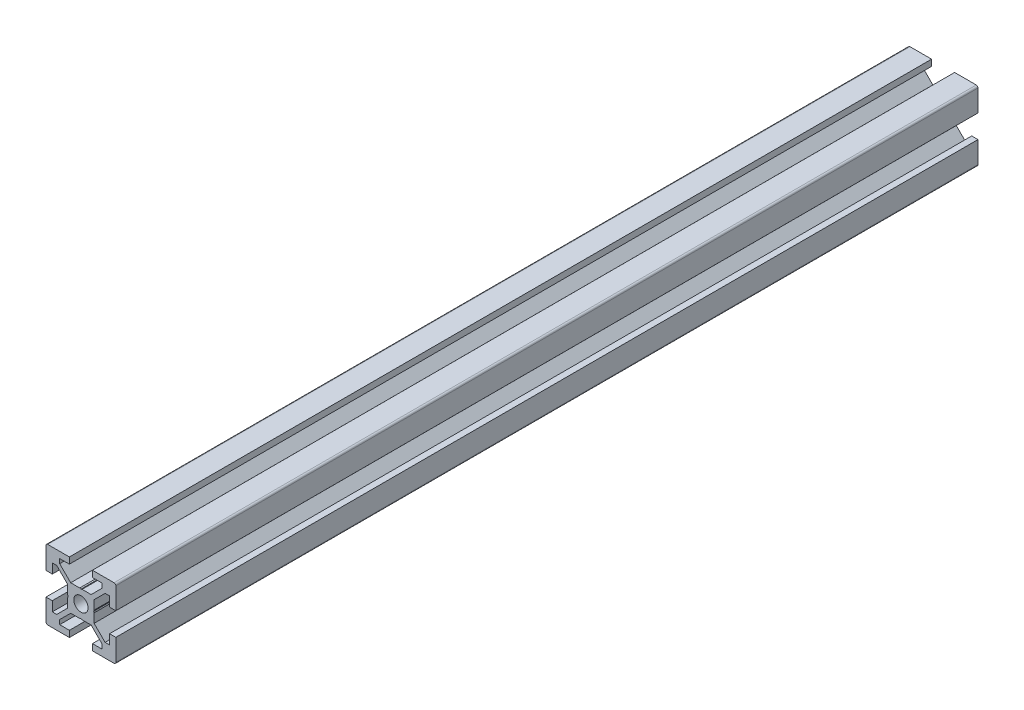
SolidWorks part; units mm, degrees
ref_plane "Front Plane" through (0, 0, 0) normal (0, 0, 1) x (1, 0, 0)
ref_plane "Top Plane" through (0, 0, 0) normal (0, 1, 0) x (1, 0, 0)
ref_plane "Right Plane" through (0, 0, 0) normal (1, 0, 0) x (0, 0, -1)
sketch "Sketch1" plane through (0, 0, 0) normal (0, 0, 1) x (1, 0, 0)
  line L0 (-3.3, 10) -> (-3.3, 8.2)
  line L1 (0, 0) -> (50000, 0) construction
  line L2 (-10, 3.3) -> (-10, 10)
  line L3 (-10, 10) -> (-3.3, 10)
  line L4 (0, 0) -> (0, 50000) construction
  line L5 (-10, -10) -> (10, 10) construction
  line L6 (-10, 10) -> (10, -10) construction
  line L7 (-2.9315, -3.78) -> (-0.34, -3.78)
  line L8 (-3.78, -2.9315) -> (-3.78, -0.34)
  line L9 (-2.9315, 3.78) -> (-0.34, 3.78)
  line L10 (3.78, -2.9315) -> (3.78, -0.34)
  line L11 (-3.78, -3.78) -> (3.78, 3.78) construction
  line L12 (-3.78, 3.78) -> (3.78, -3.78) construction
  line L13 (-6.08, 8.2) -> (-3.3, 8.2)
  line L14 (-8.2, 6.08) -> (-8.2, 3.3)
  line L15 (-8.2, 3.3) -> (-10, 3.3)
  line L16 (-8.2, 6.08) -> (-6.9285, 6.08)
  line L17 (-6.08, 8.2) -> (-6.08, 6.9285)
  line L18 (-6.9285, 6.08) -> (-3.78, 2.9315)
  line L19 (-6.08, 6.9285) -> (-2.9315, 3.78)
  line L20 (8.2, 6.08) -> (6.9285, 6.08)
  line L21 (8.2, 6.08) -> (8.2, 3.3)
  line L22 (8.2, 3.3) -> (10, 3.3)
  line L23 (10, 3.3) -> (10, 10)
  line L24 (10, 10) -> (3.3, 10)
  line L25 (3.3, 10) -> (3.3, 8.2)
  line L26 (6.08, 8.2) -> (3.3, 8.2)
  line L27 (6.08, 8.2) -> (6.08, 6.9285)
  line L28 (6.08, 6.9285) -> (2.9315, 3.78)
  line L29 (6.9285, 6.08) -> (3.78, 2.9315)
  line L30 (6.9285, -6.08) -> (3.78, -2.9315)
  line L31 (6.08, -6.9285) -> (2.9315, -3.78)
  line L32 (6.08, -8.2) -> (6.08, -6.9285)
  line L33 (6.08, -8.2) -> (3.3, -8.2)
  line L34 (3.3, -10) -> (3.3, -8.2)
  line L35 (10, -10) -> (3.3, -10)
  line L36 (10, -3.3) -> (10, -10)
  line L37 (8.2, -3.3) -> (10, -3.3)
  line L38 (8.2, -6.08) -> (8.2, -3.3)
  line L39 (8.2, -6.08) -> (6.9285, -6.08)
  line L40 (-6.08, -6.9285) -> (-2.9315, -3.78)
  line L41 (-6.9285, -6.08) -> (-3.78, -2.9315)
  line L42 (-6.08, -8.2) -> (-6.08, -6.9285)
  line L43 (-8.2, -6.08) -> (-6.9285, -6.08)
  line L44 (-8.2, -3.3) -> (-10, -3.3)
  line L45 (-8.2, -6.08) -> (-8.2, -3.3)
  line L46 (-6.08, -8.2) -> (-3.3, -8.2)
  line L47 (-10, -10) -> (-3.3, -10)
  line L48 (-10, -3.3) -> (-10, -10)
  line L49 (-3.3, -10) -> (-3.3, -8.2)
  line L50 (-0.34, 3.78) -> (0, 3.66)
  line L51 (0.34, 3.78) -> (0, 3.66)
  line L52 (0.34, 3.78) -> (2.9315, 3.78)
  line L53 (-3.78, -0.34) -> (-3.66, 0)
  line L54 (-3.78, 0.34) -> (-3.66, 0)
  line L55 (3.78, 0.34) -> (3.66, 0)
  line L56 (3.78, -0.34) -> (3.66, 0)
  line L57 (-0.34, -3.78) -> (0, -3.66)
  line L58 (0.34, -3.78) -> (0, -3.66)
  line L59 (3.78, 0.34) -> (3.78, 2.9315)
  line L60 (0.34, -3.78) -> (2.9315, -3.78)
  line L61 (-3.78, 0.34) -> (-3.78, 2.9315)
  circle A0 centre (0, 0) radius 2.05
  point P0 (0, 0)
  dimension "D3" = 4.1
  dimension "D1" = 20
  dimension "D2" = 20
  dimension "D4" = 7.56
  dimension "D5" = 6.7
  dimension "D6" = 6.7
  dimension "D7" = 0.6
  dimension "D8" = 3.92
  dimension "D9" = 0.34
  dimension "D10" = 0.12
extrude "Boss-Extrude1" add sketch "Sketch1" along normal blind 247
fillet "Fillet1" radius 0.5 4 edges at (-10, 10, 123.5) (-10, -10, 123.5) (10, -10, 123.5) (10, 10, 123.5)
